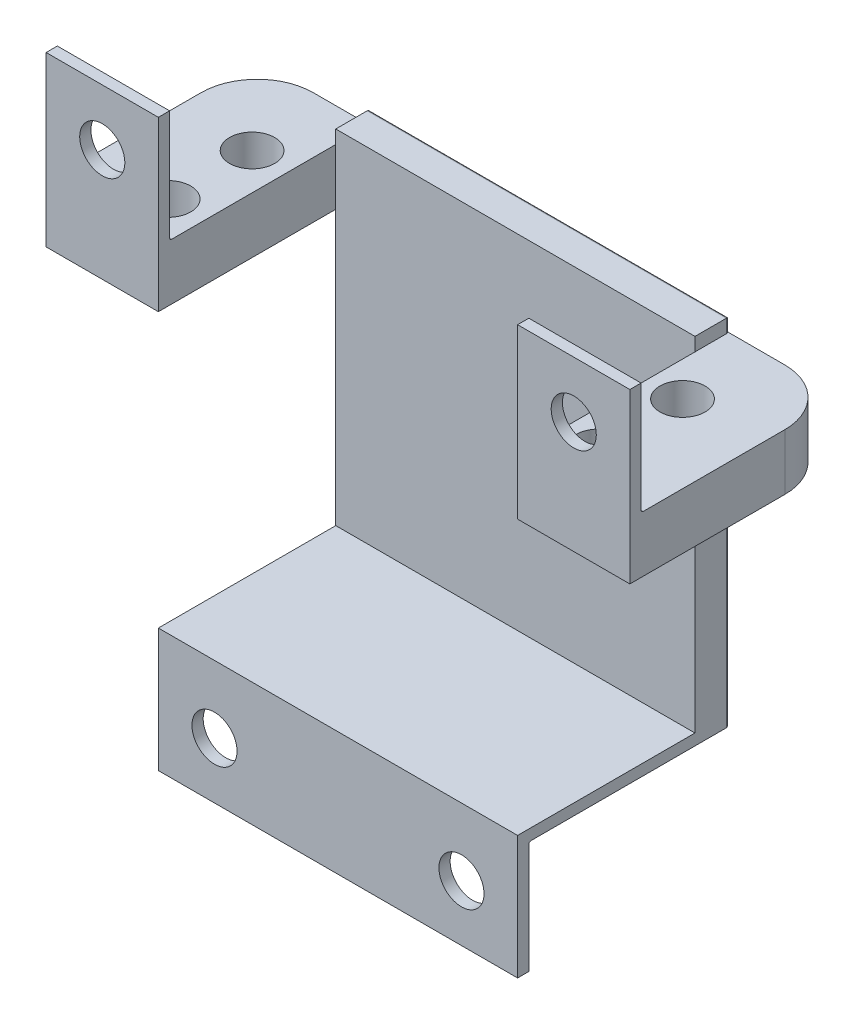
SolidWorks part; units mm, degrees
ref_plane "Front Plane" through (0, 0, 0) normal (0, 0, 1) x (1, 0, 0)
ref_plane "Top Plane" through (0, 0, 0) normal (0, 1, 0) x (1, 0, 0)
ref_plane "Right Plane" through (0, 0, 0) normal (1, 0, 0) x (0, 0, -1)
sketch "Sketch1" plane through (0, 0, 0) normal (0, 1, 0) x (1, 0, 0)
  line L1 (0, 0) -> (12.7, 0)
  line L2 (0, 0) -> (0, 18.796)
  line L3 (0, 18.796) -> (12.7, 18.796)
  line L4 (12.7, 0) -> (12.7, 18.796)
  dimension "D1" = 12.7
  dimension "D2" = 18.796
extrude "Boss-Extrude1" add sketch "Sketch1" along normal blind 6.35
sketch "Sketch2" plane through (0, 6.35, 0) normal (0, 1, 0) x (1, 0, 0)
  line L2 (0, 0) -> (12.7, 0) construction
  line L3 (6.35, 0) -> (8.89, 0) construction
  line L6 (12.7, 18.796) -> (0, 18.796) construction
  line L8 (0, 18.796) -> (0, 0) construction
  circle A9 centre (8.5526, 14.75) radius 2.5527
  circle A10 centre (8.5526, 5.25) radius 2.5527
  dimension "D1" = 5.1054
  dimension "D2" = 5.1054
  dimension "D4" = 4.046
  dimension "D3" = 9.5
  dimension "D5" = 8.5526
  dimension "D6" = 8.5526
extrude "Cut-Extrude1" cut sketch "Sketch2" against normal up to surface (6.35 mm away) up to face at (6.35, 0, -9.398)
sketch "Sketch3" plane through (0, 0, -18.796) normal (0, 0, -1) x (-1, 0, 0)
  line L6 (0, 0) -> (-66.04, 0)
  line L7 (0, 0) -> (0, 6.35)
  line L8 (0, 6.35) -> (-66.04, 6.35)
  line L9 (-66.04, 0) -> (-66.04, 6.35)
  dimension "D1" = 6.35
  dimension "D2" = 66.04
extrude "Boss-Extrude2" add sketch "Sketch3" along normal blind 5.08
sketch "Sketch4" plane through (0, 0, -23.876) normal (0, 0, -1) x (-1, 0, 0)
  line L0 (0, 6.35) -> (-66.04, 6.35) construction
  line L1 (-53.34, 6.35) -> (-12.7, 6.35)
  line L2 (-53.34, 6.35) -> (-53.34, 7.874)
  line L3 (-53.34, 7.874) -> (-12.7, 7.874)
  line L4 (-12.7, 6.35) -> (-12.7, 7.874)
  dimension "D1" = 1.524
  dimension "D2" = 40.64
  dimension "D3" = 12.7
extrude "Boss-Extrude5" add sketch "Sketch4" against normal blind 3.81
sketch "Sketch9" plane through (0, 0, -23.876) normal (0, 0, -1) x (-1, 0, 0)
  line L9 (-12.7, 7.874) -> (-12.7, 0) construction
  line L11 (-12.7, 0) -> (-53.34, 0)
  line L12 (-12.7, 0) -> (-12.7, -30.988)
  line L13 (-12.7, -30.988) -> (-53.34, -30.988)
  line L14 (-53.34, 0) -> (-53.34, -30.988)
  dimension "D1" = 40.64
  dimension "D2" = 30.988
extrude "Boss-Extrude6" add sketch "Sketch9" against normal blind 3.81
sketch "Sketch10" plane through (0, 0, -18.796) normal (0, 0, 1) x (1, 0, 0)
  line L7 (12.7, 6.35) -> (66.04, 6.35)
  line L8 (12.7, 6.35) -> (12.7, 0)
  line L9 (12.7, 0) -> (66.04, 0)
  line L10 (66.04, 6.35) -> (66.04, 0)
extrude "Cut-Extrude3" cut sketch "Sketch10" against normal up to surface (1.27 mm away) up to face at (33.02, 7.112, -20.066)
sketch "Sketch11" plane through (0, 0, 0) normal (0, 0, 1) x (1, 0, 0)
  line L17 (12.7, 0) -> (0, 0)
  line L18 (12.7, 0) -> (12.7, 19.05)
  line L19 (12.7, 19.05) -> (0, 19.05)
  line L20 (0, 0) -> (0, 19.05)
  dimension "D1" = 19.05
  dimension "D2" = 12.7
extrude "Boss-Extrude7" add sketch "Sketch11" against normal blind 1.27
sketch "Sketch16" plane through (0, 0, -1.27) normal (0, 0, -1) x (-1, 0, 0)
  line L0 (-6.35, 6.35) -> (-6.35, 19.05) construction
  line L3 (-12.7, 6.35) -> (0, 6.35) construction
  line L4 (-12.7, 19.05) -> (0, 19.05) construction
  circle A1 centre (-6.35, 12.7) radius 2.5527
  dimension "D1" = 5.1054
extrude "Cut-Extrude5" cut sketch "Sketch16" against normal up to surface (1.27 mm away) up to face at (6.35, 9.525, 0)
sketch "Sketch17" plane through (0, 0, -23.876) normal (0, 0, -1) x (-1, 0, 0)
  line L1 (-53.34, 6.35) -> (-66.04, 6.35)
  line L2 (-53.34, 6.35) -> (-53.34, 0)
  line L3 (-53.34, 0) -> (-66.04, 0)
  line L4 (-66.04, 6.35) -> (-66.04, 0)
extrude "Boss-Extrude8" add sketch "Sketch17" against normal blind 23.876
sketch "Sketch20" plane through (0, 6.35, 0) normal (0, 1, 0) x (1, 0, 0)
  line L0 (53.34, 23.876) -> (66.04, 23.876) construction
  line L1 (53.34, 0) -> (66.04, 0) construction
  line L2 (53.34, 0) -> (53.34, 20.066) construction
  circle A4 centre (57.2474, 14.75) radius 2.5527
  circle A5 centre (57.2474, 5.25) radius 2.5527
  dimension "D1" = 5.1054
  dimension "D2" = 5.1054
  dimension "D3" = 9.5
  dimension "D4" = 9.126
  dimension "D5" = 5.25
  dimension "D6" = 3.9074
extrude "Cut-Extrude6" cut sketch "Sketch20" against normal up to surface (6.35 mm away) contours A4 | A5 up to face at (58.42, 0, -13.5636)
sketch "Sketch21" plane through (0, 0, 0) normal (0, 0, 1) x (1, 0, 0)
  line L5 (66.04, 0) -> (53.34, 0)
  line L6 (66.04, 0) -> (66.04, 19.05)
  line L7 (66.04, 19.05) -> (53.34, 19.05)
  line L8 (53.34, 0) -> (53.34, 19.05)
  dimension "D1" = 12.7
  dimension "D2" = 19.05
extrude "Boss-Extrude9" add sketch "Sketch21" against normal blind 1.27
sketch "Sketch22" plane through (0, 0, -1.27) normal (0, 0, -1) x (-1, 0, 0)
  line L0 (-59.69, 19.05) -> (-59.69, 6.35) construction
  line L3 (-66.04, 19.05) -> (-53.34, 19.05) construction
  line L4 (-66.04, 6.35) -> (-53.34, 6.35) construction
  circle A1 centre (-59.69, 12.7) radius 2.5527
  dimension "D1" = 5.1054
extrude "Cut-Extrude7" cut sketch "Sketch22" against normal up to surface (1.27 mm away) up to face at (59.69, 9.525, 0)
sketch "Sketch23" plane through (0, -30.988, 0) normal (0, -1, 0) x (1, 0, 0)
  line L1 (53.34, -23.876) -> (12.7, -23.876)
  line L2 (53.34, -23.876) -> (53.34, 0)
  line L3 (53.34, 0) -> (12.7, 0)
  line L4 (12.7, -23.876) -> (12.7, 0)
  dimension "D1" = 40.64
  dimension "D2" = 23.876
extrude "Boss-Extrude10" add sketch "Sketch23" along normal blind 1.27
sketch "Sketch24" plane through (0, 0, 0) normal (0, 0, 1) x (1, 0, 0)
  line L1 (12.7, -30.988) -> (53.34, -30.988)
  line L2 (12.7, -30.988) -> (12.7, -44.958)
  line L3 (12.7, -44.958) -> (53.34, -44.958)
  line L4 (53.34, -30.988) -> (53.34, -44.958)
  dimension "D1" = 40.64
  dimension "D2" = 13.97
extrude "Boss-Extrude11" add sketch "Sketch24" against normal blind 1.27
sketch "Sketch25" plane through (0, 0, -1.27) normal (0, 0, -1) x (-1, 0, 0)
  line L0 (-53.34, -44.958) -> (-40.64, -44.958) construction
  line L1 (-12.7, -44.958) -> (-53.34, -44.958) construction
  line L2 (-40.64, -44.958) -> (-40.64, -32.258) construction
  line L3 (-12.7, -32.258) -> (-53.34, -32.258) construction
  line L4 (-40.64, -32.258) -> (-53.34, -44.958) construction
  line L5 (-25.4, -32.258) -> (-25.4, -44.958) construction
  line L6 (-53.34, -32.258) -> (-12.7, -32.258) construction
  line L7 (-25.4, -44.958) -> (-12.7, -44.958) construction
  line L8 (-12.7, -44.958) -> (-25.4, -32.258) construction
  circle A0 centre (-46.99, -38.608) radius 2.5527
  circle A1 centre (-19.05, -38.608) radius 2.5527
  dimension "D2" = 5.1054
  dimension "D4" = 5.1054
  dimension "D1" = 12.7
  dimension "D3" = 12.7
extrude "Cut-Extrude8" cut sketch "Sketch25" against normal up to surface (1.27 mm away) contours A0 | A1 up to face at (33.02, -37.973, 0)
fillet "Fillet4" radius 6.35 2 edges at (0, 3.175, -23.876) (66.04, 3.175, -23.876)
fillet "Fillet5" radius 0.254 9 edges at (33.02, -32.258, -1.27) (59.69, 6.35, -1.27) (6.35, 6.35, -1.27) (12.7, -16.129, -23.876) (33.02, -32.258, -23.876) (53.34, -16.129, -23.876) (33.02, 7.874, -23.876) (53.34, 7.112, -23.876) (12.7, 7.112, -23.876)
